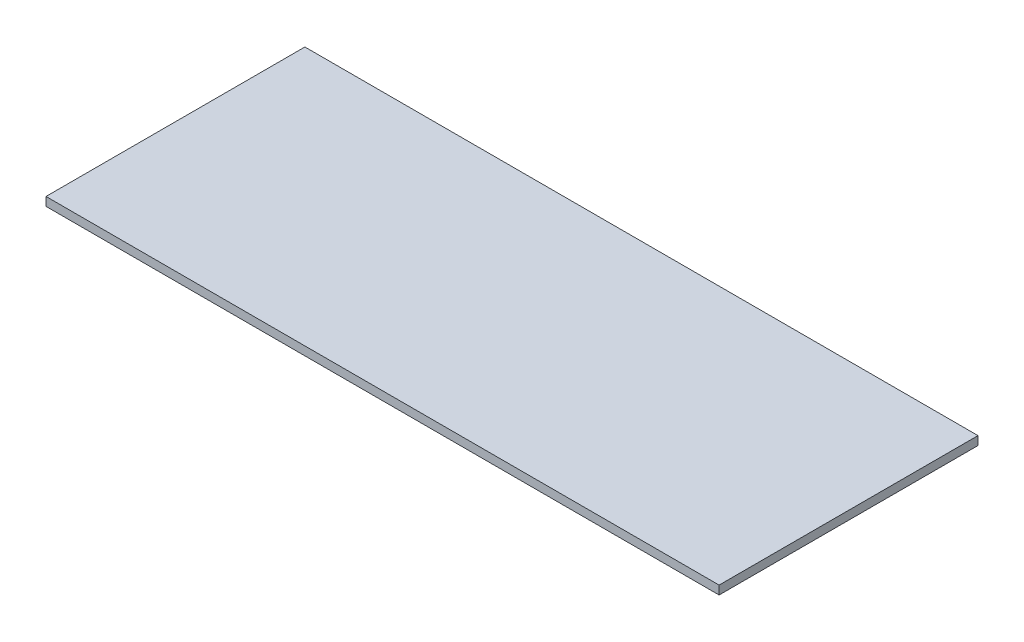
SolidWorks part; units mm, degrees
ref_plane "Front Plane" through (0, 0, 0) normal (0, 0, 1) x (1, 0, 0)
ref_plane "Top Plane" through (0, 0, 0) normal (0, 1, 0) x (1, 0, 0)
ref_plane "Right Plane" through (0, 0, 0) normal (1, 0, 0) x (0, 0, -1)
sketch "Sketch2" plane through (0, 0, 0) normal (0, 1, 0) x (1, 0, 0)
  line L1 (-990.6, -381) -> (990.6, -381)
  line L2 (-990.6, -381) -> (-990.6, 381)
  line L3 (-990.6, 381) -> (990.6, 381)
  line L4 (990.6, -381) -> (990.6, 381)
  line L5 (-990.6, -381) -> (990.6, 381) construction
  line L6 (-990.6, 381) -> (990.6, -381) construction
  point P0 (0, 0)
  dimension "D1" = 762
  dimension "D2" = 1981.2
extrude "Boss-Extrude1" add sketch "Sketch2" along normal blind 25.4
